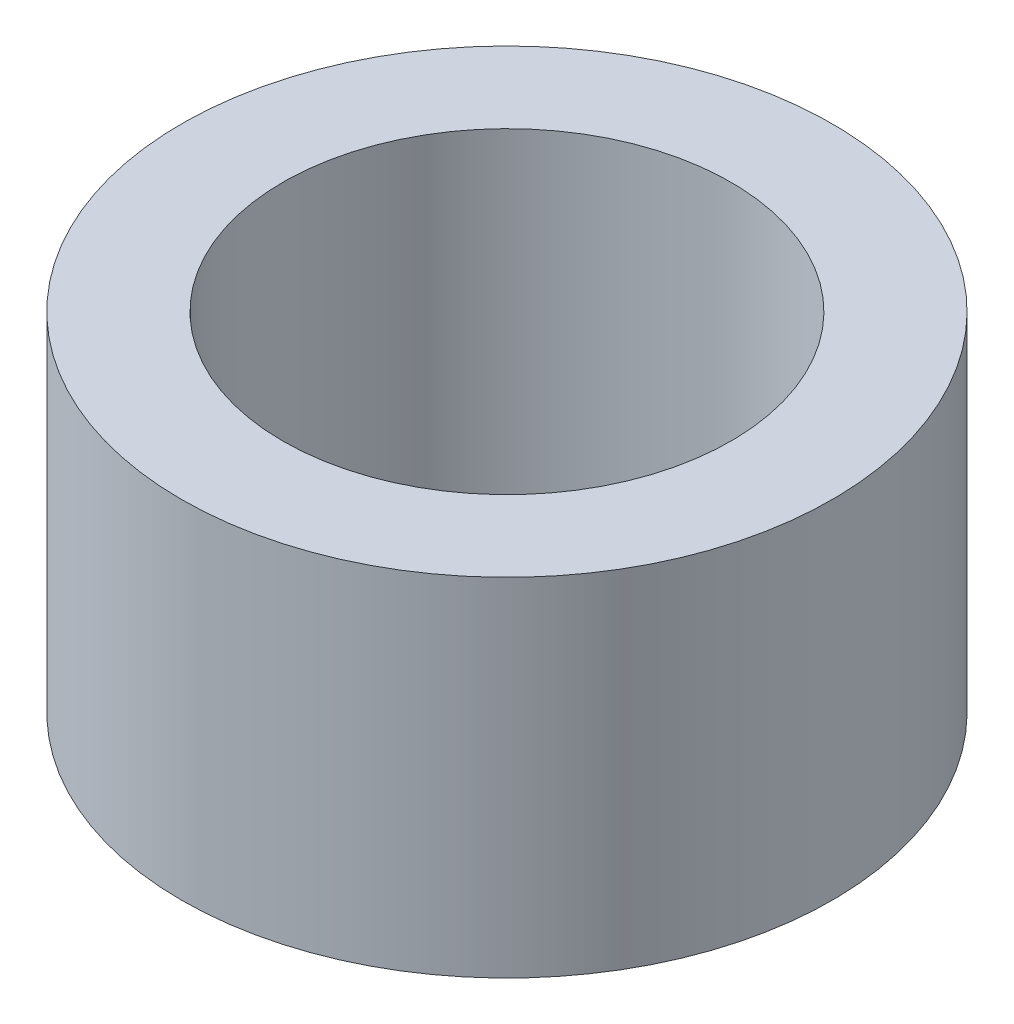
SolidWorks part; units mm, degrees
ref_plane "正面" through (0, 0, 0) normal (0, 0, 1) x (1, 0, 0)
ref_plane "平面" through (0, 0, 0) normal (0, 1, 0) x (1, 0, 0)
ref_plane "右側面" through (0, 0, 0) normal (1, 0, 0) x (0, 0, -1)
sketch "ｽｹｯﾁ1" plane through (0, 0, 0) normal (0, 1, 0) x (1, 0, 0)
  circle A0 centre (0, 0) radius 3
  circle A1 centre (0, 0) radius 4.5
  dimension "D1" = 6
  dimension "D2" = 1.5
extrude "ﾎﾞｽ - 押し出し1" add sketch "ｽｹｯﾁ1" along normal blind 4.8
other "面の移動1" face at (0, 4.8, 3) parameters "D1"=0.1
